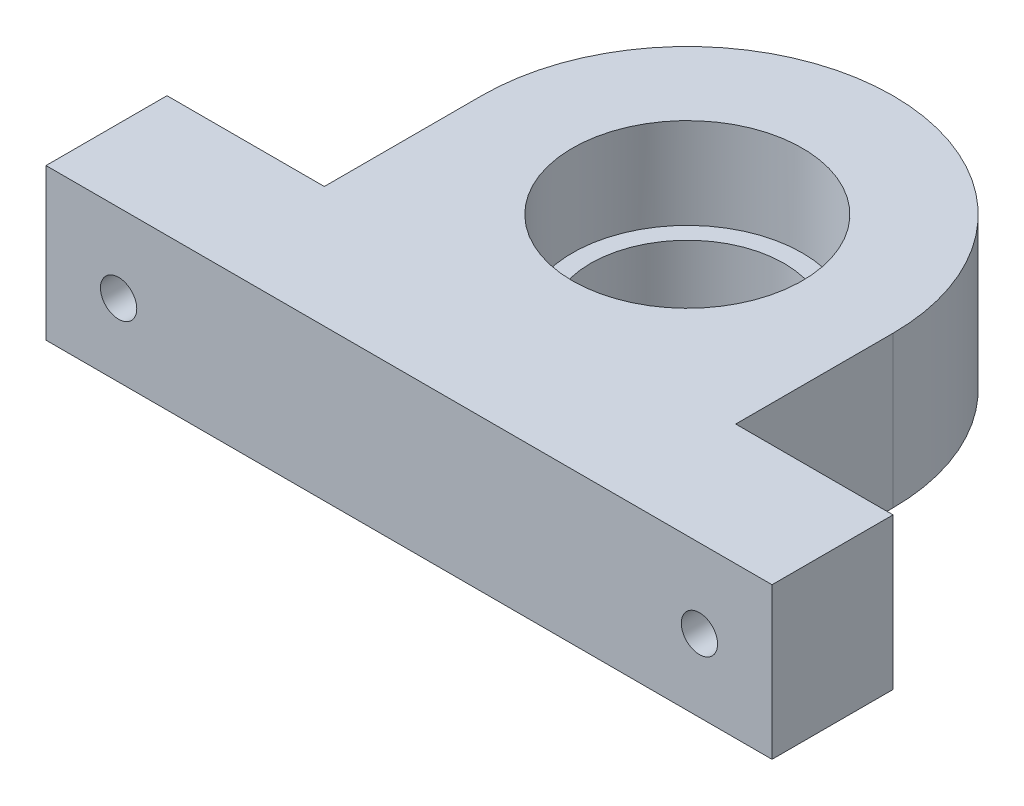
SolidWorks part; units mm, degrees
ref_plane "前视基准面" through (0, 0, 0) normal (0, 0, 1) x (1, 0, 0)
ref_plane "上视基准面" through (0, 0, 0) normal (0, 1, 0) x (1, 0, 0)
ref_plane "右视基准面" through (0, 0, 0) normal (1, 0, 0) x (0, 0, -1)
sketch "草图1" plane through (0, 0, 0) normal (0, 0, 1) x (1, 0, 0)
  line L1 (-30, 35) -> (30, 35)
  line L2 (-30, 35) -> (-30, -35)
  line L3 (-30, -35) -> (30, -35)
  line L4 (30, 35) -> (30, -35)
  line L5 (-30, 35) -> (30, -35) construction
  line L6 (-30, -35) -> (30, 35) construction
  point P0 (0, 0)
  dimension "D1" = 60
  dimension "D2" = 70
extrude "凸台-拉伸1" add sketch "草图1" along normal blind 10
sketch "草图2" plane through (0, 0, 10) normal (0, 0, 1) x (1, 0, 0)
  line L0 (0, 0) -> (24.7398, 0) construction
  line L1 (0, 15) -> (30, 15) construction
  line L3 (5.5, 0) -> (-5.5, 0) construction
  line L4 (-2.1573, -15) -> (27.8427, -15) construction
  circle A0 centre (-8, 15) radius 3
  circle A1 centre (7, 15) radius 3
  circle A2 centre (-8, -15) radius 3
  circle A3 centre (7, -15) radius 3
  circle A6 centre (22, 15) radius 3
  circle A7 centre (22, -15) radius 3
  dimension "D6" = 6
  dimension "D7" = 6
  dimension "D8" = 6
  dimension "D9" = 6
  dimension "D14" = 6
  dimension "D15" = 6
  dimension "D1" = 15
  dimension "D2" = 15
  dimension "D3" = 15
  dimension "D12" = 15
  dimension "D13" = 15
extrude "切除-拉伸1" cut sketch "草图2" against normal through all
sketch "草图3" plane through (0, 0, 0) normal (0, 0, -1) x (-1, 0, 0)
  line L0 (8, 22.5) -> (-30, 22.5)
  line L1 (8, 7.5) -> (-30, 7.5)
  line L4 (-30, 35) -> (-30, -35)
  line L5 (-30, -35) -> (30, -35)
  line L6 (30, -35) -> (30, 35)
  line L7 (30, 35) -> (-30, 35)
  line L8 (-30, 35) -> (-30, -35)
  line L9 (-30, -35) -> (30, -35)
  line L10 (30, -35) -> (30, 35)
  line L11 (30, 35) -> (-30, 35)
  circle A0 centre (8, -15) radius 3 construction
  circle A1 centre (-7, -15) radius 3 construction
  circle A2 centre (8, 15) radius 3 construction
  circle A3 centre (-7, 15) radius 3 construction
  circle A4 centre (8, -15) radius 3
  circle A5 centre (-7, -15) radius 3
  circle A6 centre (8, 15) radius 3
  circle A7 centre (-7, 15) radius 3
  circle A8 centre (8, 15) radius 7.5
  circle M7 centre (-7, 15) radius 3
  circle M10 centre (8, 15) radius 3
  line M11 (-30, 35) -> (-30, -35)
  dimension "D2" = 15
  dimension "D1" = 0
extrude "切除-拉伸2" cut sketch "草图3" against normal blind 4 contours A8 M10 | A8 L0 L1 M11 M7
mirror "镜向1" about plane through (0, 0, 0) normal (0, 1, 0) of "切除-拉伸2"
sketch "草图4" plane through (0, 0, 10) normal (0, 0, 1) x (1, 0, 0)
  line L0 (-20, 5) -> (-30, 5)
  line L1 (-20, -5) -> (-30, -5)
  line L4 (30, -35) -> (30, 35)
  line L5 (30, 35) -> (-30, 35)
  line L6 (-30, 35) -> (-30, -35)
  line L7 (-30, -35) -> (30, -35)
  line L8 (30, -35) -> (30, 35)
  line L9 (30, 35) -> (-30, 35)
  line L10 (-30, 35) -> (-30, -35)
  line L11 (-30, -35) -> (30, -35)
  circle A0 centre (-20, 0) radius 5
  line M14 (-30, 35) -> (-30, -35)
  dimension "D2" = 10
  dimension "D3" = 10
  dimension "D1" = 0
extrude "切除-拉伸3" cut sketch "草图4" against normal blind 1 contours A0 | A0 L0 L1 M14
sketch "草图6" plane through (0, 35, 0) normal (0, 1, 0) x (1, 0, 0)
  line L0 (0, -5.5) -> (0, 5.5) construction
  line L4 (30, 0) -> (-30, 0)
  line L5 (-30, 0) -> (-30, -10)
  line L6 (-30, -10) -> (30, -10)
  line L7 (30, -10) -> (30, 0)
  line L8 (30, 0) -> (-30, 0)
  line L9 (-30, 0) -> (-30, -10)
  line L10 (-30, -10) -> (30, -10)
  line L11 (30, -10) -> (30, 0)
  arc A0 (-30, 0) -> (-17, 13) centre (-30, 13) ccw
  arc A1 (-17, 13) -> (17, 13) centre (0, 13) cw
  arc A2 (30, 0) -> (17, 13) centre (30, 13) cw
  point P8 (0, 0)
  line M5 (30, 0) -> (-30, 0)
  dimension "D2" = 13
  dimension "D1" = 0
extrude "凸台-拉伸2" add sketch "草图6" against normal blind 12.5 contours A2 A1 A0 M5
sketch "草图7" plane through (0, 35, 0) normal (0, 1, 0) x (1, 0, 0)
  line L0 (0, 22.5) -> (0, 30) construction
  line L1 (-5, 29.2481) -> (-5, 21.0777)
  line L2 (5, 29.2481) -> (5, 21.0777)
  line L3 (30, -10) -> (30, 0)
  line L4 (-30, 0) -> (-30, -10)
  line L5 (-30, -10) -> (30, -10)
  line L6 (30, -10) -> (30, 0)
  line L7 (-30, 0) -> (-30, -10)
  line L8 (-30, -10) -> (30, -10)
  circle A0 centre (0, 13) radius 9.5
  arc A3 (17, 13) -> (30, 0) centre (30, 13) ccw
  arc A4 (17, 13) -> (-17, 13) centre (0, 13) ccw
  arc A5 (-30, 0) -> (-17, 13) centre (-30, 13) ccw
  arc A6 (17, 13) -> (30, 0) centre (30, 13) ccw
  arc A7 (17, 13) -> (-17, 13) centre (0, 13) ccw
  arc A8 (-30, 0) -> (-17, 13) centre (-30, 13) ccw
  dimension "D2" = 19
  dimension "D3" = 5
  dimension "D1" = 0
extrude "切除-拉伸4" cut sketch "草图7" against normal up to surface (12.5 mm away) contours A0 up to face at (2, 22.5, -4.2307)
mirror "镜向2" about plane through (0, 0, 0) normal (0, 1, 0) of "切除-拉伸4", "凸台-拉伸2"
sketch "草图8" plane through (0, -35, 0) normal (0, -1, 0) x (1, 0, 0)
  line L3 (-30, 10) -> (-30, 0)
  line L4 (30, 0) -> (30, 10)
  line L5 (30, 10) -> (-30, 10)
  line L6 (-30, 10) -> (-30, 0)
  line L7 (30, 0) -> (30, 10)
  line L8 (30, 10) -> (-30, 10)
  arc A3 (-17, -13) -> (-30, 0) centre (-30, -13) ccw
  arc A4 (-17, -13) -> (17, -13) centre (0, -13) ccw
  arc A5 (30, 0) -> (17, -13) centre (30, -13) ccw
  arc A6 (-17, -13) -> (-30, 0) centre (-30, -13) ccw
  arc A7 (-17, -13) -> (17, -13) centre (0, -13) ccw
  arc A8 (30, 0) -> (17, -13) centre (30, -13) ccw
  dimension "D1" = 0
extrude "切除-拉伸5" cut sketch "草图8" against normal up to surface (57.5 mm away) up to face at (0, 22.5, -3.5)
sketch "草图9" plane through (0, 0, 10) normal (0, 0, 1) x (1, 0, 0)
  line L4 (-30, 22.5) -> (30, 22.5)
  line L5 (30, 22.5) -> (30, 35)
  line L6 (30, 35) -> (-30, 35)
  line L7 (-30, 35) -> (-30, 22.5)
  line L8 (-30, 22.5) -> (30, 22.5)
  line L9 (30, 22.5) -> (30, 35)
  line L10 (30, 35) -> (-30, 35)
  line L11 (-30, 35) -> (-30, 22.5)
  circle A0 centre (-24, 28.5) radius 1.5
  circle A1 centre (24, 28.5) radius 1.5
  dimension "D6" = 3
  dimension "D7" = 3
  dimension "D2" = 6
  dimension "D3" = 6
  dimension "D4" = 6
  dimension "D5" = 6
  dimension "D1" = 0
extrude "切除-拉伸6" cut sketch "草图9" against normal through all contours A1 | A0
sketch "草图10" plane through (30, 0, 0) normal (1, 0, 0) x (0, 0, -1)
  line L0 (13, 22.5) -> (13, 35) construction
  line L1 (13, 22.5) -> (13, 35)
  line L2 (0, 35) -> (13, 35)
  line L3 (0, 22.5) -> (13, 22.5)
  line L4 (-10, 35) -> (-10, 22.5)
  line L5 (-10, 22.5) -> (0, 22.5)
  line L6 (0, 22.5) -> (0, 35)
  line L7 (0, 35) -> (-10, 35)
  line L8 (-10, 35) -> (-10, 22.5)
  line L9 (-10, 22.5) -> (0, 22.5)
  line L10 (0, 22.5) -> (0, 35)
  line L11 (0, 35) -> (-10, 35)
  line M7 (0, 22.5) -> (0, 35)
  dimension "D1" = 0
extrude "切除-拉伸7" cut sketch "草图10" against normal up to vertex (13 mm away) contours L3 L1 L2 M7
sketch "草图11" plane through (-30, 0, 0) normal (-1, 0, 0) x (0, 0, 1)
  line L0 (-13, 22.5) -> (-13, 35) construction
  line L1 (-13, 22.5) -> (-13, 35)
  line L2 (0, 35) -> (-13, 35)
  line L3 (0, 22.5) -> (-13, 22.5)
  line L4 (0, 35) -> (0, 22.5)
  line L5 (0, 22.5) -> (10, 22.5)
  line L6 (10, 22.5) -> (10, 35)
  line L7 (10, 35) -> (0, 35)
  line L8 (0, 35) -> (0, 22.5)
  line L9 (0, 22.5) -> (10, 22.5)
  line L10 (10, 22.5) -> (10, 35)
  line L11 (10, 35) -> (0, 35)
  line M5 (0, 35) -> (0, 22.5)
  dimension "D1" = 0
extrude "切除-拉伸8" cut sketch "草图11" against normal blind 13 contours L3 L2 L1 M5
sketch "草图12" plane through (0, 22.5, 0) normal (0, -1, 0) x (1, 0, 0)
  circle A0 centre (0, -13) radius 9.5 construction
  circle A1 centre (0, -13) radius 9.5
  circle A2 centre (0, -13) radius 8
  dimension "D1" = 16
extrude "凸台-拉伸3" add sketch "草图12" against normal blind 5
